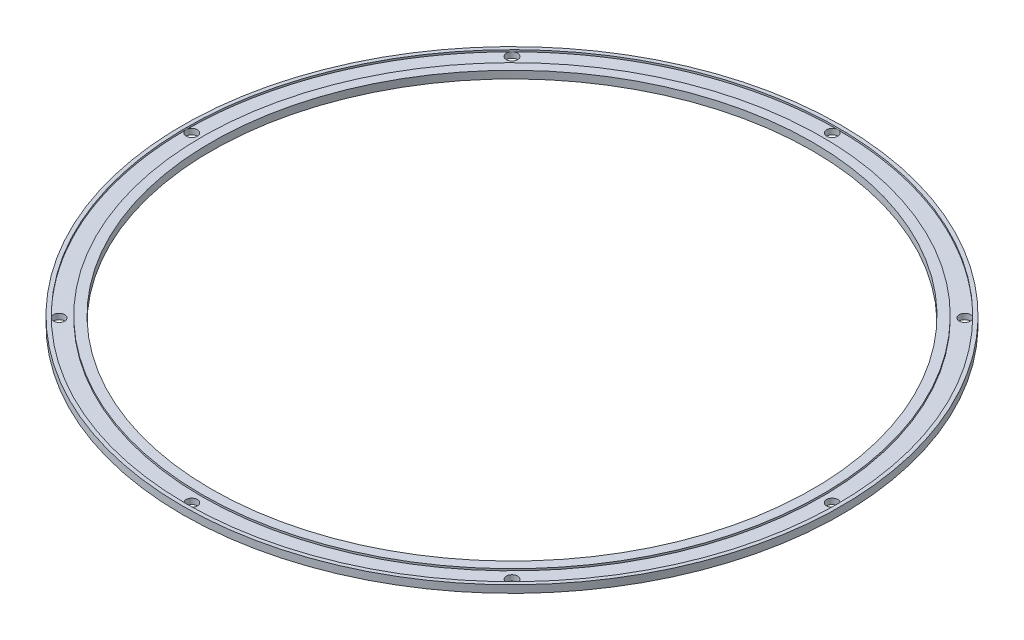
SolidWorks part; units mm, degrees
material "6061-T6 (SS)"
ref_plane "前视基准面" through (0, 0, 0) normal (0, 0, 1) x (1, 0, 0)
ref_plane "上视基准面" through (0, 0, 0) normal (0, 1, 0) x (1, 0, 0)
ref_plane "右视基准面" through (0, 0, 0) normal (1, 0, 0) x (0, 0, -1)
sketch "草图1" plane through (0, 0, 0) normal (0, 0, 1) x (1, 0, 0)
  line L0 (-169.7756, 0) -> (180.6818, 0) construction
  line L1 (0, 155.5974) -> (0, -144.6182) construction
  line L2 (80.25, 0) -> (88, 0)
  line L3 (88, 0) -> (88, 2)
  line L6 (82.75, 2) -> (80.25, 2)
  line L7 (80.25, 2) -> (80.25, 0)
  line L8 (82.75, 2) -> (82.75, 1.5)
  line L9 (82.75, 1.5) -> (87, 1.5)
  line L10 (87, 1.5) -> (87, 2)
  line L11 (87, 2) -> (88, 2)
  dimension "D1" = 160.5
  dimension "D2" = 176
  dimension "D3" = 0.5
  dimension "D4" = 2
  dimension "D5" = 2.5
  dimension "D6" = 1
revolve "旋转1" add sketch "草图1" angle 360 about L1
sketch "草图2" plane through (0, 1.5, 0) normal (0, 1, 0) x (1, 0, 0)
  circle A0 centre (0, 0) radius 85.5 construction
  circle A1 centre (0, 85.5) radius 1.5
  circle A2 centre (60.4576, 60.4576) radius 1.5
  circle A3 centre (85.5, 0) radius 1.5
  circle A4 centre (60.4576, -60.4576) radius 1.5
  circle A5 centre (0, -85.5) radius 1.5
  circle A6 centre (-60.4576, -60.4576) radius 1.5
  circle A7 centre (-85.5, 0) radius 1.5
  circle A8 centre (-60.4576, 60.4576) radius 1.5
  point P21 (0, 0)
  dimension "D1" = 171
  dimension "D2" = 3
  dimension "D3" = 8
extrude "切除-拉伸1" cut sketch "草图2" against normal through all
move or copy body "实体-移动/复制1" [suppressed] bodies to move or copy 107
